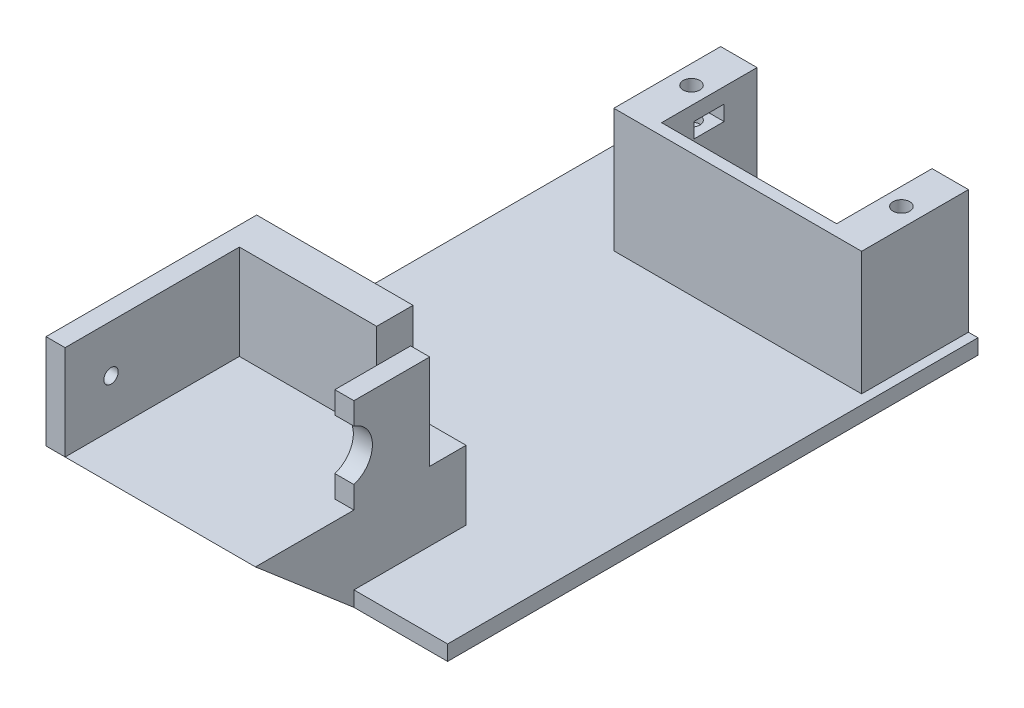
SolidWorks part; units mm, degrees
ref_plane "Front Plane" through (0, 0, 0) normal (0, 0, 1) x (1, 0, 0)
ref_plane "Top Plane" through (0, 0, 0) normal (0, 1, 0) x (1, 0, 0)
ref_plane "Right Plane" through (0, 0, 0) normal (1, 0, 0) x (0, 0, -1)
sketch "Sketch1" plane through (0, 0, 0) normal (0, 1, 0) x (1, 0, 0)
  line L1 (-23, -35) -> (23, -35)
  line L2 (-23, -35) -> (-23, 35)
  line L3 (-23, 35) -> (23, 35)
  line L4 (23, -35) -> (23, 35)
  line L5 (-23, -35) -> (23, 35) construction
  line L6 (-23, 35) -> (23, -35) construction
  point P0 (0, 0)
  dimension "D1" = 46
  dimension "D2" = 70
extrude "Boss-Extrude1" add sketch "Sketch1" along normal blind 2
sketch "Sketch2" plane through (0, 2, 0) normal (0, 1, 0) x (1, 0, 0)
  line L0 (23, 35) -> (-23, 35) construction
  line L1 (-6.16, 35) -> (16.94, 35) construction
  line L2 (-6.16, 35) -> (-6.16, 22.4) construction
  line L3 (-6.16, 22.4) -> (16.94, 22.4) construction
  line L4 (16.94, 35) -> (16.94, 22.4) construction
  line L5 (-6.16, 35) -> (16.94, 22.4) construction
  line L6 (-6.16, 22.4) -> (16.94, 35) construction
  line L7 (16.94, 22.4) -> (16.94, 35)
  line L8 (16.94, 35) -> (21.74, 35)
  line L9 (21.74, 35) -> (21.74, 20.9)
  line L10 (21.74, 20.9) -> (-10.96, 20.9)
  line L11 (-10.96, 20.9) -> (-10.96, 35)
  line L12 (-10.96, 35) -> (-6.16, 35)
  line L13 (-6.16, 35) -> (-6.16, 22.4)
  line L14 (-6.16, 22.4) -> (16.94, 22.4)
  point P0 (5.39, 28.7)
  dimension "D1" = 12.6
  dimension "D2" = 16.94
  dimension "D3" = 23.1
  dimension "D4" = 21.74
  dimension "D5" = 1.5
extrude "Boss-Extrude2" add sketch "Sketch2" along normal offset from surface (16.3 mm away) 18.3 up to face at (0, 0, 0)
sketch "Sketch3" plane through (0, 2, 0) normal (0, 1, 0) x (1, 0, 0)
  line L4 (16.94, 22.4) -> (16.94, 35)
  line L5 (16.94, 35) -> (-6.16, 35)
  line L6 (-6.16, 35) -> (-6.16, 22.4)
  line L7 (-6.16, 22.4) -> (16.94, 22.4)
  line L8 (16.94, 22.4) -> (16.94, 35)
  line L9 (16.94, 35) -> (-6.16, 35)
  line L10 (-6.16, 35) -> (-6.16, 22.4)
  line L11 (-6.16, 22.4) -> (16.94, 22.4)
  dimension "D1" = 0
extrude "Cut-Extrude1" cut sketch "Sketch3" against normal through all
sketch "Sketch4" plane through (0, 0, 0) normal (0, -1, 0) x (1, 0, 0)
  line L0 (-23, 35) -> (23, 35) construction
  line L1 (-17, 20.2) -> (17, 20.2)
  line L2 (-17, 20.2) -> (-17, 35)
  line L3 (-17, 35) -> (17, 35)
  line L4 (17, 20.2) -> (17, 35)
  line L5 (-17, 20.2) -> (17, 35) construction
  line L6 (-17, 35) -> (17, 20.2) construction
  point P0 (0, 27.6)
  dimension "D1" = 34
  dimension "D2" = 14.8
extrude "Boss-Extrude3" add sketch "Sketch4" against normal blind 11.125
sketch "Sketch5" plane through (0, 11.125, 0) normal (0, 1, 0) x (1, 0, 0)
  line L0 (17, -35) -> (-17, -35) construction
  line L1 (8.12, -35) -> (-14.48, -35) construction
  line L2 (8.12, -35) -> (8.12, -25) construction
  line L3 (8.12, -25) -> (-14.48, -25) construction
  line L4 (-14.48, -35) -> (-14.48, -25) construction
  line L5 (-14.48, -35) -> (-17, -35)
  line L6 (-17, -35) -> (-17, -20.2)
  line L7 (-17, -20.2) -> (10.64, -20.2)
  line L8 (-17, -20.2) -> (17, -20.2) construction
  line L9 (10.64, -20.2) -> (10.64, -35)
  line L10 (10.64, -35) -> (8.12, -35)
  line L11 (-14.48, -35) -> (-14.48, -25)
  line L12 (-14.48, -25) -> (8.12, -25)
  line L13 (8.12, -25) -> (8.12, -35)
  dimension "D1" = 14.48
  dimension "D2" = 22.6
  dimension "D3" = 10
extrude "Boss-Extrude4" add sketch "Sketch5" along normal blind 12.5
sketch "Sketch7" plane through (0, 11.125, 0) normal (0, 1, 0) x (1, 0, 0)
  line L4 (10.64, -20.2) -> (10.64, -35)
  line L5 (10.64, -35) -> (17, -35)
  line L6 (17, -35) -> (17, -20.2)
  line L7 (17, -20.2) -> (10.64, -20.2)
  line L8 (10.64, -20.2) -> (10.64, -35)
  line L9 (10.64, -35) -> (17, -35)
  line L10 (17, -35) -> (17, -20.2)
  line L11 (17, -20.2) -> (10.64, -20.2)
  dimension "D1" = 0
extrude "Cut-Extrude2" cut sketch "Sketch7" against normal up to surface (9.125 mm away) up to face at (1.7967, 2, -0.1167)
sketch "Sketch8" plane through (-14.48, 0, 0) normal (1, 0, 0) x (0, 0, -1)
  line L0 (-35, 23.625) -> (-25, 23.625) construction
  line L1 (-35, 11.125) -> (-48, 11.125)
  line L2 (-35, 11.125) -> (-35, 23.625)
  line L3 (-35, 23.625) -> (-48, 23.625)
  line L4 (-48, 11.125) -> (-48, 23.625)
  line L5 (-25, 23.625) -> (-25, 11.125) construction
  circle A0 centre (-41.939, 17.375) radius 0.95
  point P10 (-48, 17.375)
  dimension "D2" = 1.9
  dimension "D1" = 6.939
  dimension "D3" = 23
extrude "Boss-Extrude5" add sketch "Sketch8" against normal up to surface (2.52 mm away) up to face at (-17, 12.8125, 27.6)
sketch "Sketch9" plane through (-17, 0, 0) normal (-1, 0, 0) x (0, 0, 1)
  line L0 (48, 11.125) -> (35, 0)
  line L1 (35, 0) -> (35, 11.125)
  line L2 (35, 11.125) -> (48, 11.125)
extrude "Boss-Extrude6" add sketch "Sketch9" against normal up to surface (27.64 mm away) up to face at (10.64, 12.8125, 27.6)
sketch "Sketch10" plane through (0, 23.625, 0) normal (0, 1, 0) x (1, 0, 0)
  line L0 (10.64, -20.2) -> (-17, -20.2) construction
  line L1 (10.64, -20.2) -> (3.64, -20.2)
  line L2 (10.64, -20.2) -> (10.64, -25)
  line L3 (10.64, -25) -> (3.64, -25)
  line L4 (3.64, -20.2) -> (3.64, -25)
  line L5 (-14.48, -25) -> (8.12, -25) construction
  line L6 (10.64, -35) -> (10.64, -20.2) construction
  dimension "D1" = 7
extrude "Cut-Extrude3" cut sketch "Sketch10" against normal up to surface (12.5 mm away) up to face at (1.4267, 11.125, 36)
sketch "Sketch11" plane through (10.64, 0, 0) normal (1, 0, 0) x (0, 0, -1)
  line L0 (-35, 23.625) -> (-35, 11.125) construction
  line L1 (-35, 23.625) -> (-25, 23.625) construction
  circle A0 centre (-36.06, 17.375) radius 3.5
  dimension "D3" = 7
  dimension "D1" = 1.06
  dimension "D2" = 6.25
extrude "Cut-Extrude4" cut sketch "Sketch11" against normal blind 10
sketch "Sketch12" plane through (3.64, 0, 0) normal (1, 0, 0) x (0, 0, -1)
  line L0 (-25, 11.125) -> (-25, 23.625) construction
  line L1 (-35, 23.625) -> (-25, 23.625) construction
  circle A0 centre (-22.62, 17.375) radius 1.1
  dimension "D1" = 2.2
  dimension "D2" = 2.38
  dimension "D3" = 6.25
extrude "Cut-Extrude5" cut sketch "Sketch12" against normal blind 8
ref_plane "Plane1" through (1.64, 0, 0) normal (1, 0, 0) x (0, 0, -1)
sketch "Sketch13" plane through (1.64, 0, 0) normal (1, 0, 0) x (0, 0, -1)
  line L0 (-21.4942, 19.325) -> (-19.2, 19.325)
  line L1 (-20.3683, 17.375) -> (-21.4942, 19.325) construction
  line L2 (-21.4942, 19.325) -> (-23.7458, 19.325)
  line L3 (-23.7458, 19.325) -> (-24.8717, 17.375)
  line L4 (-24.8717, 17.375) -> (-23.7458, 15.425)
  line L5 (-23.7458, 15.425) -> (-21.4942, 15.425)
  line L6 (-21.4942, 15.425) -> (-20.3683, 17.375) construction
  line L7 (-19.2, 19.325) -> (-19.2, 15.425)
  line L8 (-19.2, 15.425) -> (-21.4942, 15.425)
  line L9 (-20.2, 11.125) -> (-20.2, 23.625) construction
  circle A0 centre (-22.62, 17.375) radius 1.95 construction
  circle A2 centre (-22.62, 17.375) radius 1.1 construction
  dimension "D1" = 3.9
  dimension "D2" = 1
extrude "Cut-Extrude6" cut sketch "Sketch13" against normal blind 1.8
sketch "Sketch14" plane through (0, 18.3, 0) normal (0, 1, 0) x (1, 0, 0)
  line L0 (16.94, 35) -> (21.74, 35) construction
  line L1 (16.94, 22.4) -> (16.94, 35) construction
  circle A0 centre (-8.46, 28.65) radius 1.1
  circle A1 centre (19.24, 28.65) radius 1.1
  point P8 (0, 0)
  dimension "D1" = 2.2
  dimension "D2" = 6.35
  dimension "D3" = 2.3
  dimension "D4" = 27.7
extrude "Cut-Extrude7" cut sketch "Sketch14" against normal blind 5
ref_plane "Plane2" through (0, 16.3, 0) normal (0, 1, 0) x (1, 0, 0)
sketch "Sketch15" plane through (0, 16.3, 0) normal (0, 1, 0) x (1, 0, 0)
  line L0 (18.0853, 30.65) -> (16.94, 30.65)
  line L1 (16.9306, 28.65) -> (18.0853, 26.65) construction
  line L2 (18.0853, 26.65) -> (20.3947, 26.65)
  line L3 (20.3947, 26.65) -> (21.5494, 28.65)
  line L4 (21.5494, 28.65) -> (20.3947, 30.65)
  line L5 (20.3947, 30.65) -> (18.0853, 30.65)
  line L6 (18.0853, 30.65) -> (16.9306, 28.65) construction
  line L7 (16.94, 30.65) -> (16.94, 26.65)
  line L8 (16.94, 26.65) -> (18.0853, 26.65)
  line L9 (16.94, 22.4) -> (16.94, 35) construction
  line L10 (5.39, 20.9) -> (5.39, 34.6081) construction
  line L11 (-10.96, 20.9) -> (21.74, 20.9) construction
  line L12 (-7.3053, 30.65) -> (-6.1506, 28.65) construction
  line L13 (-6.1506, 28.65) -> (-7.3053, 26.65) construction
  line L14 (-6.16, 26.65) -> (-7.3053, 26.65)
  line L15 (-6.16, 30.65) -> (-6.16, 26.65)
  line L16 (-9.6147, 30.65) -> (-7.3053, 30.65)
  line L17 (-10.7694, 28.65) -> (-9.6147, 30.65)
  line L18 (-9.6147, 26.65) -> (-10.7694, 28.65)
  line L19 (-7.3053, 26.65) -> (-9.6147, 26.65)
  line L20 (-7.3053, 30.65) -> (-6.16, 30.65)
  circle A0 centre (19.24, 28.65) radius 2 construction
  circle A2 centre (19.24, 28.65) radius 1.1 construction
  circle A3 centre (-8.46, 28.65) radius 2 construction
  point P18 (0, 0)
  dimension "D1" = 4
extrude "Cut-Extrude8" cut sketch "Sketch15" against normal blind 2
